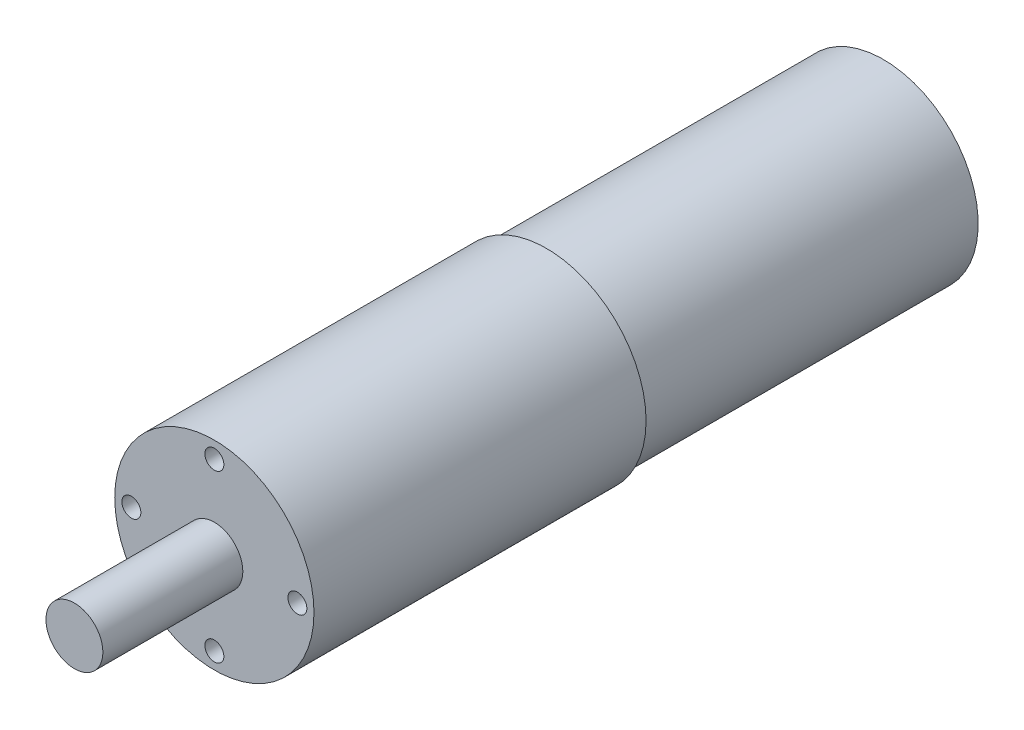
SolidWorks part; units mm, degrees
ref_plane "Płaszczyzna przednia" through (0, 0, 0) normal (0, 0, 1) x (1, 0, 0)
ref_plane "Płaszczyzna górna" through (0, 0, 0) normal (0, 1, 0) x (1, 0, 0)
ref_plane "Płaszczyzna prawa" through (0, 0, 0) normal (1, 0, 0) x (0, 0, -1)
sketch "Szkic1" plane through (0, 0, 0) normal (0, 0, 1) x (1, 0, 0)
  circle A0 centre (0, 0) radius 21
  dimension "D1" = 42
extrude "Dodanie-wyciągnięcie1" add sketch "Szkic1" along normal blind 70
sketch "Szkic2" plane through (0, 0, 70) normal (0, 0, 1) x (1, 0, 0)
  circle A0 centre (0, 0) radius 17.5 construction
  circle A1 centre (0, 17.5) radius 2
  circle A2 centre (17.5, 0) radius 2
  circle A3 centre (0, -17.5) radius 2
  circle A4 centre (-17.5, 0) radius 2
  point P14 (0, 0)
  dimension "D1" = 35
  dimension "D2" = 4
  dimension "D3" = 4
extrude "Wytnij-wyciągnięcie1" cut sketch "Szkic2" against normal blind 6
sketch "Szkic3" plane through (0, 0, 70) normal (0, 0, 1) x (1, 0, 0)
  circle A0 centre (0, 0) radius 6
  dimension "D1" = 12
extrude "Dodanie-wyciągnięcie2" add sketch "Szkic3" along normal blind 29.5
sketch "Szkic4" plane through (0, 0, 0) normal (0, 0, -1) x (-1, 0, 0)
  circle A0 centre (0, 0) radius 20
  dimension "D1" = 40
extrude "Dodanie-wyciągnięcie3" add sketch "Szkic4" along normal blind 71
